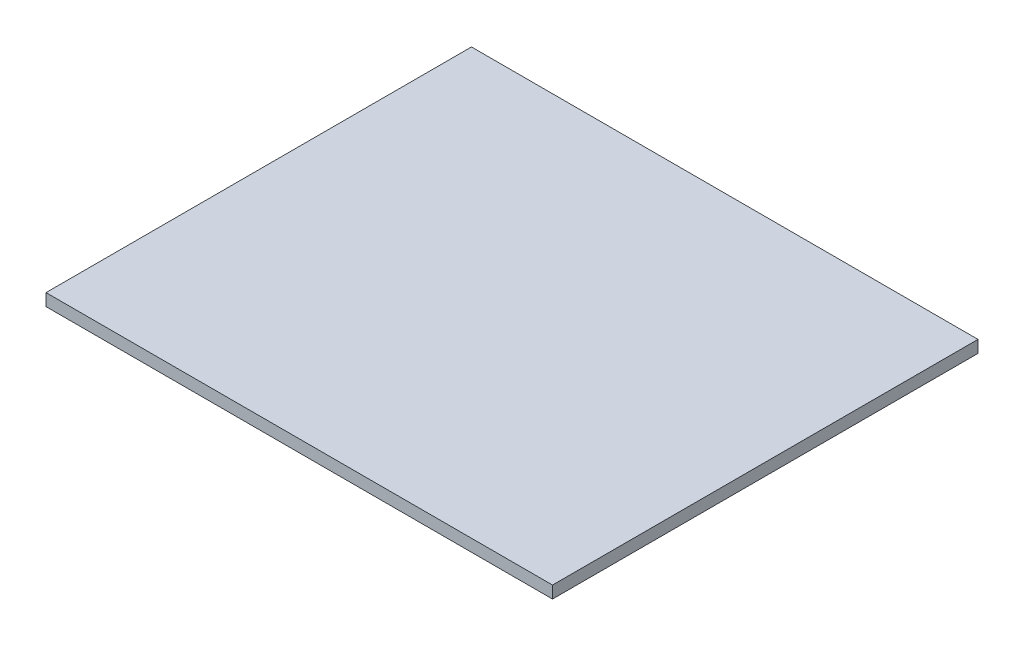
SolidWorks part; units mm, degrees
ref_plane "Front Plane" through (0, 0, 0) normal (0, 0, 1) x (1, 0, 0)
ref_plane "Top Plane" through (0, 0, 0) normal (0, 1, 0) x (1, 0, 0)
ref_plane "Right Plane" through (0, 0, 0) normal (1, 0, 0) x (0, 0, -1)
sketch "Sketch1" plane through (0, 0, 0) normal (0, 1, 0) x (1, 0, 0)
  line L0 (62.5, -80) -> (62.5, 80) construction
  line L1 (-62.5, -75) -> (62.5, -75)
  line L2 (-62.5, -75) -> (-62.5, 30)
  line L3 (-62.5, 30) -> (62.5, 30)
  line L4 (62.5, -75) -> (62.5, 30)
  line L5 (-62.5, -75) -> (62.5, 30) construction
  line L6 (-62.5, 30) -> (62.5, -75) construction
  line L7 (62.5, 80) -> (-62.5, 80) construction
  line L8 (-62.5, 80) -> (-62.5, -80) construction
  line L9 (62.5, -80) -> (62.5, 80) construction
  line L10 (62.5, 80) -> (-62.5, 80) construction
  line L11 (-62.5, 80) -> (-62.5, -80) construction
  line L12 (52.5, 70) -> (-52.5, 70) construction
  line L13 (52.5, 70) -> (-52.5, 70) construction
  line L15 (-52.5, -80) -> (52.5, -80) construction
  line L16 (-52.5, -80) -> (52.5, -80) construction
  point P0 (0, -22.5)
  point P6 (-58.751, 77.0634)
  point P7 (-59.5278, 77.6086)
  point P10 (0, 0)
  point P13 (-62.5, 68.7328)
  point P14 (-62.5, 51.2284)
  point P18 (62.5, 30)
  dimension "D1" = 40
  dimension "D2" = 5
extrude "Boss-Extrude1" add sketch "Sketch1" along normal blind 3
